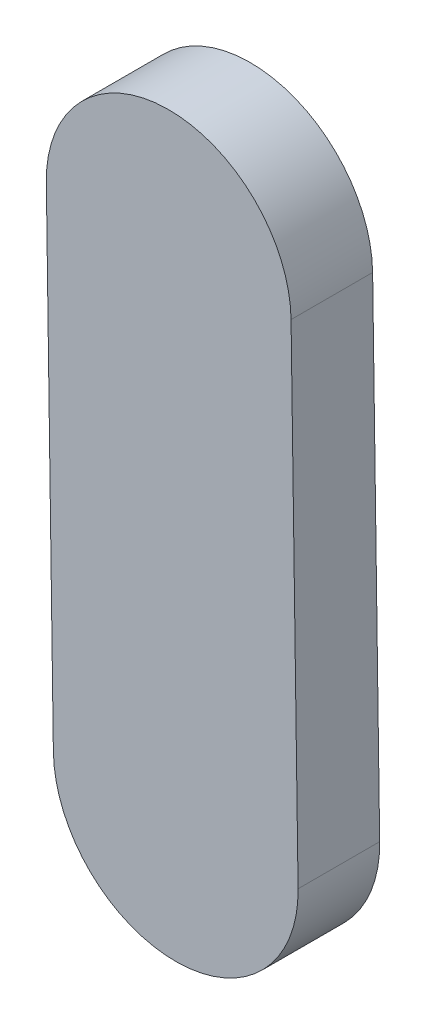
SolidWorks part; units mm, degrees
ref_plane "前视基准面" through (0, 0, 0) normal (0, 0, 1) x (1, 0, 0)
ref_plane "上视基准面" through (0, 0, 0) normal (0, 1, 0) x (1, 0, 0)
ref_plane "右视基准面" through (0, 0, 0) normal (1, 0, 0) x (0, 0, -1)
other "Configuration Table"
sketch "草图1" plane through (0, 0, 0) normal (0, 0, 1) x (1, 0, 0)
  line L0 (-3.8772, 6.2169) -> (-3.7911, 0.2169) construction
  line L1 (-2.3772, 6.2385) -> (-2.2911, 0.2385)
  line L2 (-5.3772, 6.1954) -> (-5.2911, 0.1954)
  arc A0 (-2.3772, 6.2385) -> (-5.3772, 6.1954) centre (-3.8772, 6.2169) ccw
  arc A1 (-5.2911, 0.1954) -> (-2.2911, 0.2385) centre (-3.7911, 0.2169) ccw
  point P2 (-3.8342, 3.2169)
  dimension "D1" = 6
  dimension "D2" = 3
extrude "凸台-拉伸1" add sketch "草图1" along normal blind 1
